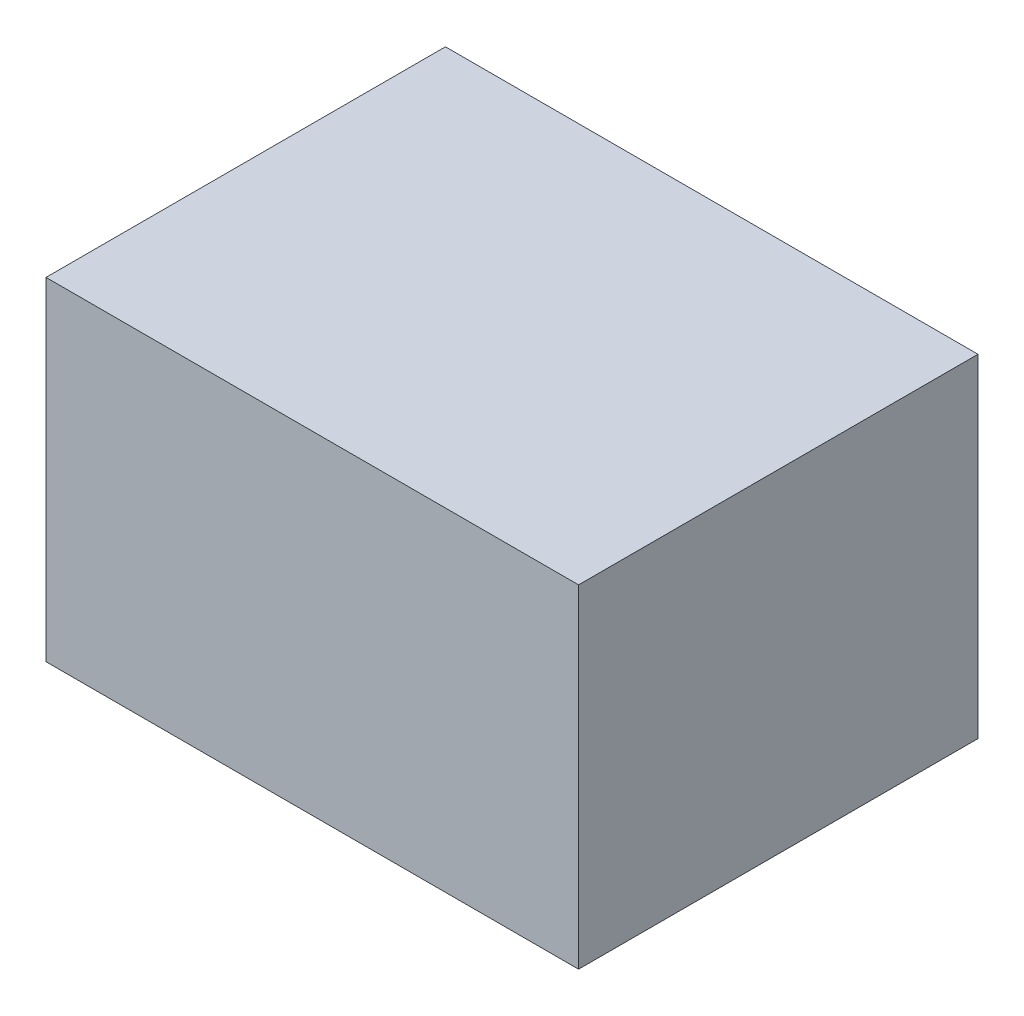
SolidWorks part; units mm, degrees
ref_plane "Front Plane" through (0, 0, 0) normal (0, 0, 1) x (1, 0, 0)
ref_plane "Top Plane" through (0, 0, 0) normal (0, 1, 0) x (1, 0, 0)
ref_plane "Right Plane" through (0, 0, 0) normal (1, 0, 0) x (0, 0, -1)
sketch "Sketch1" plane through (0, 0, 0) normal (0, 0, 1) x (1, 0, 0)
  line L0 (1, -0.625) -> (-1, -0.625)
  line L1 (-1, -0.625) -> (-1, 0.625)
  line L2 (-1, 0.625) -> (1, 0.625)
  line L3 (1, 0.625) -> (1, -0.625)
extrude "Component_Outline" add sketch "Sketch1" along normal blind 1.5 separate body
sketch3d "3DSketch1"
  line L0 (0, 0, 0) -> (1, 0, 0)
  line L1 (0, 0, 0) -> (0, 1, 0)
  line L2 (0, 0, 0) -> (0, 0, 1)
  point P0 (0, 0, 0)
